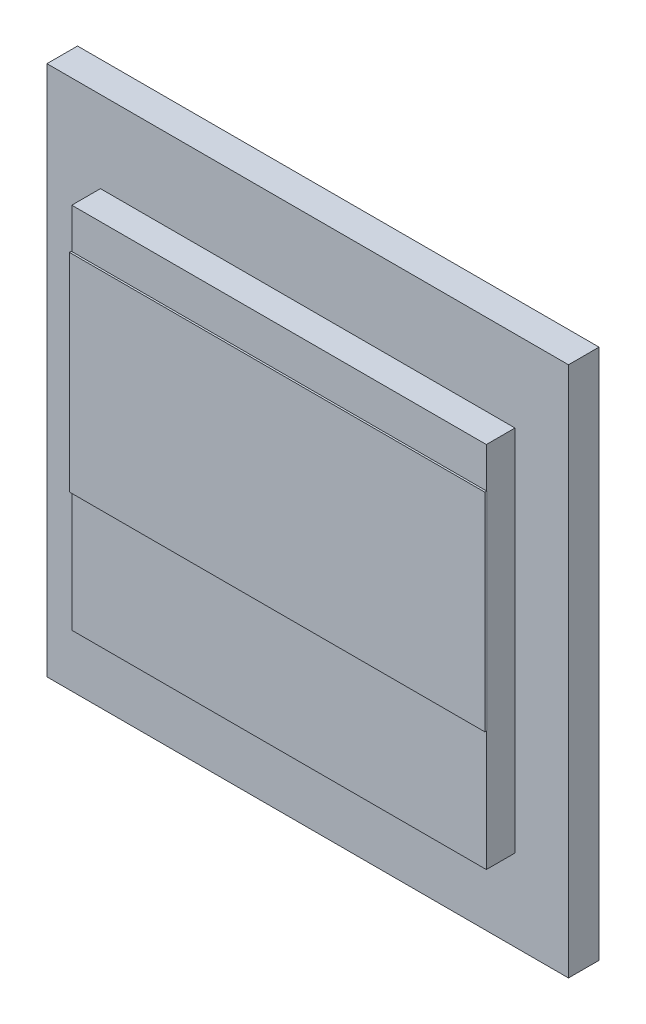
SolidWorks part; units mm, degrees
ref_plane "前视基准面" through (0, 0, 0) normal (0, 0, 1) x (1, 0, 0)
ref_plane "上视基准面" through (0, 0, 0) normal (0, 1, 0) x (1, 0, 0)
ref_plane "右视基准面" through (0, 0, 0) normal (1, 0, 0) x (0, 0, -1)
sketch "草图1" plane through (0, 0, 0) normal (0, 0, 1) x (1, 0, 0)
  line L0 (-31.8674, 0) -> (28.7375, 0) construction
  line L1 (-13.65, 13.9) -> (13.65, 13.9)
  line L2 (-13.65, 13.9) -> (-13.65, -13.9)
  line L3 (-13.65, -13.9) -> (13.65, -13.9)
  line L4 (13.65, 13.9) -> (13.65, -13.9)
  line L5 (0, -21.6346) -> (0, 24.0522) construction
  dimension "D1" = 27.3
  dimension "D2" = 27.8
extrude "凸台-拉伸1" add sketch "草图1" along normal blind 1.6
sketch "草图2" plane through (0, 0, 1.6) normal (0, 0, 1) x (1, 0, 0)
  line L0 (0, 16.2915) -> (0, -17.1684) construction
  line L1 (-10.85, 9.634) -> (10.85, 9.634)
  line L2 (-10.85, 9.634) -> (-10.85, -9.634)
  line L3 (-10.85, -9.634) -> (10.85, -9.634)
  line L4 (10.85, 9.634) -> (10.85, -9.634)
  line L5 (-17.1003, 0) -> (17.5064, 0) construction
  dimension "D1" = 21.7
  dimension "D2" = 19.268
extrude "凸台-拉伸2" add sketch "草图2" along normal blind 1.5
sketch "草图3" plane through (0, 0, 3.1) normal (0, 0, 1) x (1, 0, 0)
  line L0 (0, 15.6169) -> (0, -16.6962) construction
  line L1 (-10.872, 7.534) -> (10.872, 7.534)
  line L2 (-10.872, 7.534) -> (-10.872, -3.33)
  line L3 (-10.872, -3.33) -> (10.872, -3.33)
  line L4 (10.872, 7.534) -> (10.872, -3.33)
  line L5 (10.85, 9.634) -> (-10.85, 9.634) construction
  dimension "D1" = 10.864
  dimension "D2" = 21.744
  dimension "D3" = 2.1
extrude "凸台-拉伸3" add sketch "草图3" along normal blind 0.1
